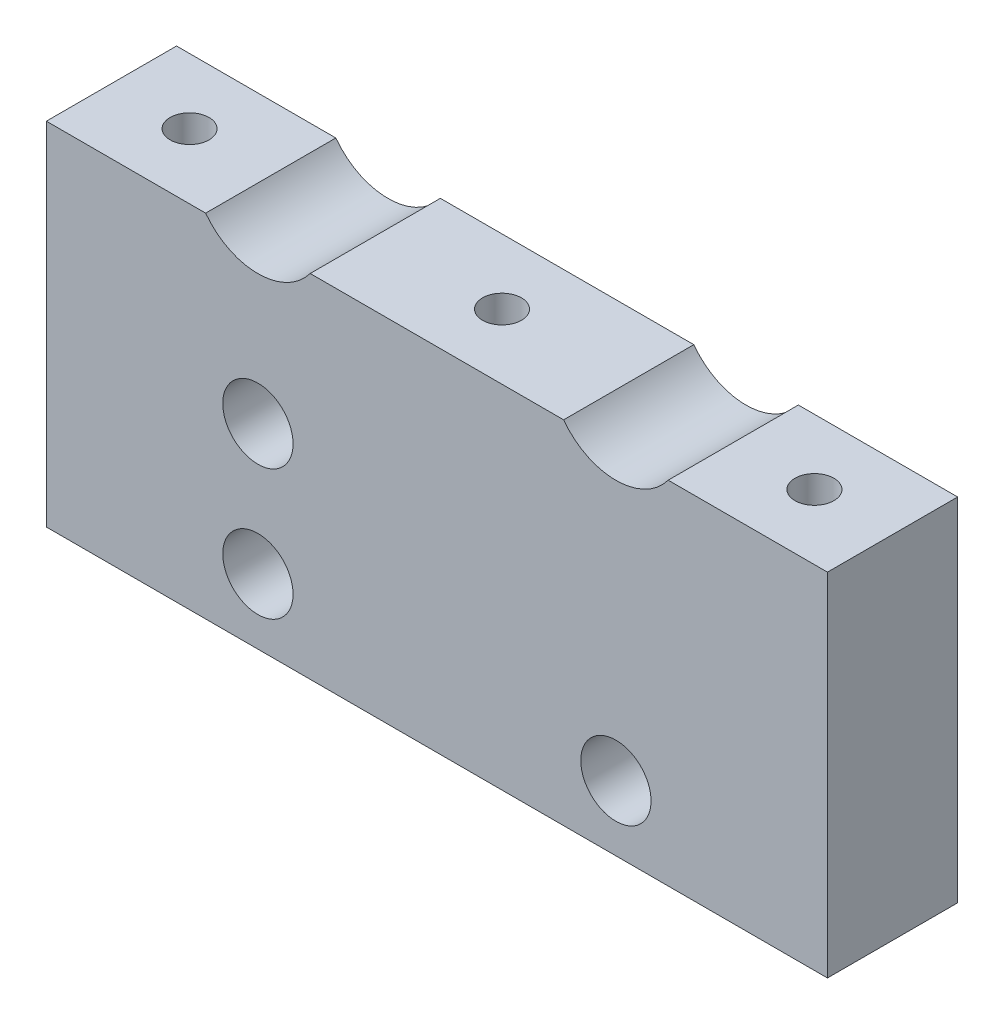
SolidWorks part; units mm, degrees
material "6061-T6 (SS)"
ref_plane "Front Plane" through (0, 0, 0) normal (0, 0, 1) x (1, 0, 0)
ref_plane "Top Plane" through (0, 0, 0) normal (0, 1, 0) x (1, 0, 0)
ref_plane "Right Plane" through (0, 0, 0) normal (1, 0, 0) x (0, 0, -1)
sketch "Sketch1" plane through (0, 0, 0) normal (0, 0, 1) x (1, 0, 0)
  line L0 (-38.1, 17.145) -> (-38.1, 24.7142) construction
  line L1 (-38.1, -17.145) -> (38.1, -17.145)
  line L2 (-38.1, -17.145) -> (-38.1, 17.145)
  line L3 (-38.1, 17.145) -> (-22.5615, 17.145)
  line L4 (38.1, -17.145) -> (38.1, 17.145)
  line L5 (-38.1, -17.145) -> (38.1, 17.145) construction
  line L6 (-38.1, 17.145) -> (38.1, -17.145) construction
  line L7 (-38.1, 24.7142) -> (38.1, 24.7142) construction
  line L8 (-38.1, 24.7142) -> (-38.1, 33.6042) construction
  line L9 (-38.1, 33.6042) -> (38.1, 33.6042) construction
  line L10 (-38.1, 20.9296) -> (38.1, 20.9296) construction
  line L11 (0, 33.6042) -> (0, -17.145) construction
  line L12 (-12.3635, 17.145) -> (12.3635, 17.145)
  line L13 (22.5615, 17.145) -> (38.1, 17.145)
  arc A0 (-11.1125, 20.9296) -> (-23.8125, 20.9296) centre (-17.4625, 20.9296) ccw construction
  arc A1 (22.5615, 17.145) -> (12.3635, 17.145) centre (17.4625, 20.9296) cw
  arc A2 (-22.5615, 17.145) -> (-12.3635, 17.145) centre (-17.4625, 20.9296) ccw
  arc A3 (11.1125, 20.9296) -> (23.8125, 20.9296) centre (17.4625, 20.9296) cw construction
  circle A4 centre (-17.4625, -10.795) radius 3.429
  circle A5 centre (17.4625, -10.795) radius 3.429
  circle A6 centre (-17.4625, 1.905) radius 3.429
  point P0 (0, 0)
  dimension "D5" = 12.7
  dimension "D6" = 34.925
  dimension "D7" = 6.35
  dimension "D8" = 6.858
  dimension "D9" = 6.858
  dimension "D10" = 19.05
  dimension "D1" = 76.2
  dimension "D2" = 34.29
  dimension "D3" = 8.89
  dimension "D4" = 7.5692
extrude "Boss-Extrude1" add sketch "Sketch1" along normal blind 12.7
sketch "Sketch2" plane through (0, 17.145, 0) normal (0, 1, 0) x (1, 0, 0)
  line L0 (-38.1, -6.35) -> (38.1, -6.35) construction
  line L1 (-38.1, -12.7) -> (-38.1, 0) construction
  line L2 (38.1, -12.7) -> (38.1, 0) construction
  point P6 (-30.48, -6.35)
  point P7 (0, -6.35)
  point P8 (30.48, -6.35)
  dimension "D1" = 7.62
  dimension "D2" = 7.62
hole_wizard "#10-24 Tapped Hole1" positions "Sketch2" profile "Sketch3" tap size "#10-24" standard "ANSI Inch"
sketch "Sketch3" plane through (30.48, 17.145, 6.35) normal (1, 0, 0) x (0, 0, 1)
  line L0 (0, 0) -> (0, 20.1908)
  line L1 (0, 20.1908) -> (1.8986, 19.05)
  line L2 (1.8986, 19.05) -> (1.8986, 0)
  line L5 (1.8986, 0) -> (0, 0)
  line L10 (0, 20.1908) -> (-1.8986, 19.05) construction
  line L11 (0, -6.35) -> (0, 107.95) construction
  dimension "Tap Drill Dia." = 3.7973
  dimension "Tap Drill Depth" = 19.05
  dimension "Drill Angle" = 118
cosmetic thread "Hole Thread1" parameters "D1"=9.652, "D2"=4.826
cosmetic thread "Hole Thread2" parameters "D1"=9.652, "D2"=4.826
cosmetic thread "Hole Thread3" parameters "D1"=9.652, "D2"=4.826
